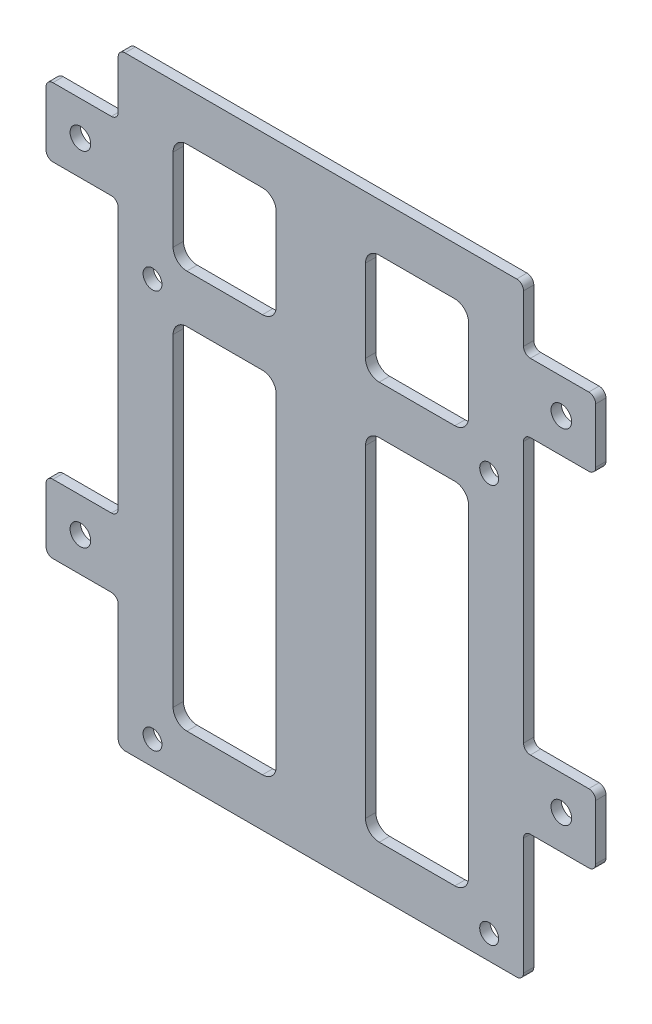
SolidWorks part; units mm, degrees
ref_plane "Спереди" through (0, 0, 0) normal (0, 0, 1) x (1, 0, 0)
ref_plane "Сверху" through (0, 0, 0) normal (0, 1, 0) x (1, 0, 0)
ref_plane "Справа" through (0, 0, 0) normal (1, 0, 0) x (0, 0, -1)
sketch "Model" plane through (0, 0, 0) normal (0, 0, 1) x (1, 0, 0)
  line L0 (-28.5, 7.5359) -> (28.5, 7.5359)
  line L1 (28.5, -80.4641) -> (-28.5, -80.4641)
  line L2 (-39, -61.4641) -> (-30.5, -61.4641)
  line L3 (-39, -51.4641) -> (-30.5, -51.4641)
  line L4 (-40, -56.4641) -> (-40, -60.4641)
  line L5 (-40, -56.4641) -> (-40, -52.4641)
  line L6 (-38, -1.4641) -> (-31.5, -1.4641)
  line L7 (-38, -11.4641) -> (-31.5, -11.4641)
  line L8 (-40, -6.4641) -> (-40, -3.4641)
  line L9 (-40, -6.4641) -> (-40, -9.4641)
  line L10 (-39, -1.4641) -> (-30.5, -1.4641)
  line L11 (-39, -11.4641) -> (-30.5, -11.4641)
  line L12 (-40, -6.4641) -> (-40, -2.4641)
  line L13 (-40, -6.4641) -> (-40, -10.4641)
  line L14 (-29.5, -79.4641) -> (-29.5, -62.4641)
  line L15 (38, -1.4641) -> (31.5, -1.4641)
  line L16 (38, -11.4641) -> (31.5, -11.4641)
  line L17 (40, -6.4641) -> (40, -3.4641)
  line L18 (40, -6.4641) -> (40, -9.4641)
  line L19 (38, -1.4641) -> (31.5, -1.4641)
  line L20 (38, -11.4641) -> (31.5, -11.4641)
  line L21 (40, -6.4641) -> (40, -3.4641)
  line L22 (40, -6.4641) -> (40, -9.4641)
  line L23 (38, -1.4641) -> (31.5, -1.4641)
  line L24 (38, -11.4641) -> (31.5, -11.4641)
  line L25 (40, -6.4641) -> (40, -3.4641)
  line L26 (40, -6.4641) -> (40, -9.4641)
  line L27 (39, -1.4641) -> (30.5, -1.4641)
  line L28 (39, -11.4641) -> (30.5, -11.4641)
  line L29 (40, -6.4641) -> (40, -2.4641)
  line L30 (40, -6.4641) -> (40, -10.4641)
  line L31 (29.5, -79.4641) -> (29.5, -62.4641)
  line L32 (0, 9.5359) -> (0, -82.4641) construction
  line L33 (38, -61.4641) -> (31.5, -61.4641)
  line L34 (38, -51.4641) -> (31.5, -51.4641)
  line L35 (40, -56.4641) -> (40, -59.4641)
  line L36 (40, -56.4641) -> (40, -53.4641)
  line L37 (39, -61.4641) -> (30.5, -61.4641)
  line L38 (39, -51.4641) -> (30.5, -51.4641)
  line L39 (40, -56.4641) -> (40, -60.4641)
  line L40 (40, -56.4641) -> (40, -52.4641)
  line L41 (29.5, -49.4641) -> (29.5, -12.4641)
  line L42 (29.5, -50.4641) -> (29.5, -12.4641)
  line L43 (-29.5, -50.4641) -> (-29.5, -12.4641)
  line L44 (-29.5, 6.5359) -> (-29.5, -0.4641)
  line L45 (29.5, 6.5359) -> (29.5, -0.4641)
  line L46 (-21.5, -42.7141) -> (-21.5, -71.7141)
  line L47 (-19.5, -73.4641) -> (-8.5, -73.4641)
  line L48 (-6.5, -71.7141) -> (-6.5, -42.7141)
  line L49 (-19.5, -73.4641) -> (-8.5, -73.4641)
  line L50 (21.5, -42.7141) -> (21.5, -71.7141)
  line L51 (19.5, -73.4641) -> (8.5, -73.4641)
  line L52 (6.5, -71.7141) -> (6.5, -42.7141)
  line L53 (19.5, -73.4641) -> (8.5, -73.4641)
  line L54 (21.5, -42.7141) -> (21.5, -71.7141)
  line L55 (19.5, -73.4641) -> (8.5, -73.4641)
  line L56 (6.5, -71.7141) -> (6.5, -42.7141)
  line L57 (19.5, -73.4641) -> (8.5, -73.4641)
  line L58 (-21.5, -53.2141) -> (-21.5, -24.2141)
  line L59 (-19.5, -22.4641) -> (-8.5, -22.4641)
  line L60 (-6.5, -24.2141) -> (-6.5, -53.2141)
  line L61 (-19.5, -22.4641) -> (-8.5, -22.4641)
  line L62 (21.5, -53.2141) -> (21.5, -24.2141)
  line L63 (19.5, -22.4641) -> (8.5, -22.4641)
  line L64 (6.5, -24.2141) -> (6.5, -53.2141)
  line L65 (19.5, -22.4641) -> (8.5, -22.4641)
  line L66 (21.5, -53.2141) -> (21.5, -24.2141)
  line L67 (19.5, -22.4641) -> (8.5, -22.4641)
  line L68 (6.5, -24.2141) -> (6.5, -53.2141)
  line L69 (19.5, -22.4641) -> (8.5, -22.4641)
  line L70 (19.5, -15.4641) -> (8.5, -15.4641)
  line L71 (6.5, -13.7141) -> (6.5, -1.4641)
  line L72 (19.5, -15.4641) -> (8.5, -15.4641)
  line L73 (21.5, -1.4641) -> (21.5, -13.7141)
  line L74 (19.5, -15.4641) -> (8.5, -15.4641)
  line L75 (6.5, -13.7141) -> (6.5, -1.4641)
  line L76 (19.5, -15.4641) -> (8.5, -15.4641)
  line L77 (8.5, 0.5359) -> (19.5, 0.5359)
  line L78 (21.5, -1.4641) -> (21.5, -13.7141)
  line L79 (-19.5, -15.4641) -> (-8.5, -15.4641)
  line L80 (-6.5, -13.7141) -> (-6.5, -1.4641)
  line L81 (-19.5, -15.4641) -> (-8.5, -15.4641)
  line L82 (-21.5, -1.4641) -> (-21.5, -13.7141)
  line L83 (-19.5, -15.4641) -> (-8.5, -15.4641)
  line L84 (-6.5, -13.7141) -> (-6.5, -1.4641)
  line L85 (-19.5, -15.4641) -> (-8.5, -15.4641)
  line L86 (-8.5, 0.5359) -> (-19.5, 0.5359)
  line L87 (-21.5, -1.4641) -> (-21.5, -13.7141)
  line L88 (-19.5, -15.4641) -> (-8.5, -15.4641)
  line L89 (-6.5, -13.7141) -> (-6.5, -1.4641)
  line L90 (-19.5, -15.4641) -> (-8.5, -15.4641)
  line L91 (-21.5, -1.4641) -> (-21.5, -13.7141)
  line L92 (-19.5, -15.4641) -> (-8.5, -15.4641)
  line L93 (-6.5, -13.7141) -> (-6.5, -1.4641)
  line L94 (-19.5, -15.4641) -> (-8.5, -15.4641)
  line L95 (-8.5, 0.5359) -> (-19.5, 0.5359)
  line L96 (-21.5, -1.4641) -> (-21.5, -13.7141)
  circle A0 centre (-35, -56.4641) radius 1.5
  circle A1 centre (-35, -6.4641) radius 1.5
  circle A2 centre (-35, -6.4641) radius 1.5
  circle A3 centre (35, -6.4641) radius 1.5
  circle A4 centre (35, -6.4641) radius 1.5
  circle A5 centre (35, -6.4641) radius 1.5
  circle A6 centre (35, -56.4641) radius 1.5
  circle A7 centre (35, -56.4641) radius 1.5
  arc A8 (-39, -1.4641) -> (-40, -2.4641) centre (-39, -2.4641) ccw
  arc A9 (-40, -10.4641) -> (-39, -11.4641) centre (-39, -10.4641) ccw
  arc A10 (-39, -51.4641) -> (-40, -52.4641) centre (-39, -52.4641) ccw
  arc A11 (-40, -60.4641) -> (-39, -61.4641) centre (-39, -60.4641) ccw
  arc A12 (-29.5, -62.4641) -> (-30.5, -61.4641) centre (-30.5, -62.4641) ccw
  arc A13 (-30.5, -51.4641) -> (-29.5, -50.4641) centre (-30.5, -50.4641) ccw
  arc A14 (-29.5, -79.4641) -> (-28.5, -80.4641) centre (-28.5, -79.4641) ccw
  arc A15 (28.5, -80.4641) -> (29.5, -79.4641) centre (28.5, -79.4641) ccw
  arc A16 (30.5, -61.4641) -> (29.5, -62.4641) centre (30.5, -62.4641) ccw
  arc A17 (29.5, -50.4641) -> (30.5, -51.4641) centre (30.5, -50.4641) ccw
  arc A18 (40, -52.4641) -> (39, -51.4641) centre (39, -52.4641) ccw
  arc A19 (39, -61.4641) -> (40, -60.4641) centre (39, -60.4641) ccw
  arc A20 (-28.5, 7.5359) -> (-29.5, 6.5359) centre (-28.5, 6.5359) ccw
  arc A21 (29.5, 6.5359) -> (28.5, 7.5359) centre (28.5, 6.5359) ccw
  arc A22 (40, -2.4641) -> (39, -1.4641) centre (39, -2.4641) ccw
  arc A23 (39, -11.4641) -> (40, -10.4641) centre (39, -10.4641) ccw
  arc A24 (-29.5, -12.4641) -> (-30.5, -11.4641) centre (-30.5, -12.4641) ccw
  arc A25 (30.5, -11.4641) -> (29.5, -12.4641) centre (30.5, -12.4641) ccw
  arc A26 (-30.5, -1.4641) -> (-29.5, -0.4641) centre (-30.5, -0.4641) ccw
  arc A27 (29.5, -0.4641) -> (30.5, -1.4641) centre (30.5, -0.4641) ccw
  circle A28 centre (-24.5, -18.9641) radius 1.375
  circle A29 centre (24.5, -18.9641) radius 1.375
  circle A30 centre (-24.5, -76.9641) radius 1.375
  circle A31 centre (24.5, -76.9641) radius 1.375
  arc A32 (-21.5, -71.4641) -> (-19.5, -73.4641) centre (-19.5, -71.4641) ccw
  arc A33 (-8.5, -73.4641) -> (-6.5, -71.4641) centre (-8.5, -71.4641) ccw
  arc A34 (19.5, -73.4641) -> (21.5, -71.4641) centre (19.5, -71.4641) ccw
  arc A35 (6.5, -71.4641) -> (8.5, -73.4641) centre (8.5, -71.4641) ccw
  arc A36 (19.5, -73.4641) -> (21.5, -71.4641) centre (19.5, -71.4641) ccw
  arc A37 (6.5, -71.4641) -> (8.5, -73.4641) centre (8.5, -71.4641) ccw
  arc A38 (-19.5, -22.4641) -> (-21.5, -24.4641) centre (-19.5, -24.4641) ccw
  arc A39 (-6.5, -24.4641) -> (-8.5, -22.4641) centre (-8.5, -24.4641) ccw
  arc A40 (21.5, -24.4641) -> (19.5, -22.4641) centre (19.5, -24.4641) ccw
  arc A41 (8.5, -22.4641) -> (6.5, -24.4641) centre (8.5, -24.4641) ccw
  arc A42 (21.5, -24.4641) -> (19.5, -22.4641) centre (19.5, -24.4641) ccw
  arc A43 (8.5, -22.4641) -> (6.5, -24.4641) centre (8.5, -24.4641) ccw
  arc A44 (19.5, -15.4641) -> (21.5, -13.4641) centre (19.5, -13.4641) ccw
  arc A45 (6.5, -13.4641) -> (8.5, -15.4641) centre (8.5, -13.4641) ccw
  arc A46 (19.5, -15.4641) -> (21.5, -13.4641) centre (19.5, -13.4641) ccw
  arc A47 (6.5, -13.4641) -> (8.5, -15.4641) centre (8.5, -13.4641) ccw
  arc A48 (8.5, 0.5359) -> (6.5, -1.4641) centre (8.5, -1.4641) ccw
  arc A49 (21.5, -1.4641) -> (19.5, 0.5359) centre (19.5, -1.4641) ccw
  arc A50 (-21.5, -13.4641) -> (-19.5, -15.4641) centre (-19.5, -13.4641) ccw
  arc A51 (-8.5, -15.4641) -> (-6.5, -13.4641) centre (-8.5, -13.4641) ccw
  arc A52 (-21.5, -13.4641) -> (-19.5, -15.4641) centre (-19.5, -13.4641) ccw
  arc A53 (-8.5, -15.4641) -> (-6.5, -13.4641) centre (-8.5, -13.4641) ccw
  arc A54 (-6.5, -1.4641) -> (-8.5, 0.5359) centre (-8.5, -1.4641) ccw
  arc A55 (-19.5, 0.5359) -> (-21.5, -1.4641) centre (-19.5, -1.4641) ccw
  arc A56 (-21.5, -13.4641) -> (-19.5, -15.4641) centre (-19.5, -13.4641) ccw
  arc A57 (-8.5, -15.4641) -> (-6.5, -13.4641) centre (-8.5, -13.4641) ccw
  arc A58 (-21.5, -13.4641) -> (-19.5, -15.4641) centre (-19.5, -13.4641) ccw
  arc A59 (-8.5, -15.4641) -> (-6.5, -13.4641) centre (-8.5, -13.4641) ccw
  arc A60 (-6.5, -1.4641) -> (-8.5, 0.5359) centre (-8.5, -1.4641) ccw
  arc A61 (-19.5, 0.5359) -> (-21.5, -1.4641) centre (-19.5, -1.4641) ccw
extrude "Бобышка-Вытянуть1" add sketch "Model" along normal blind 1.5
